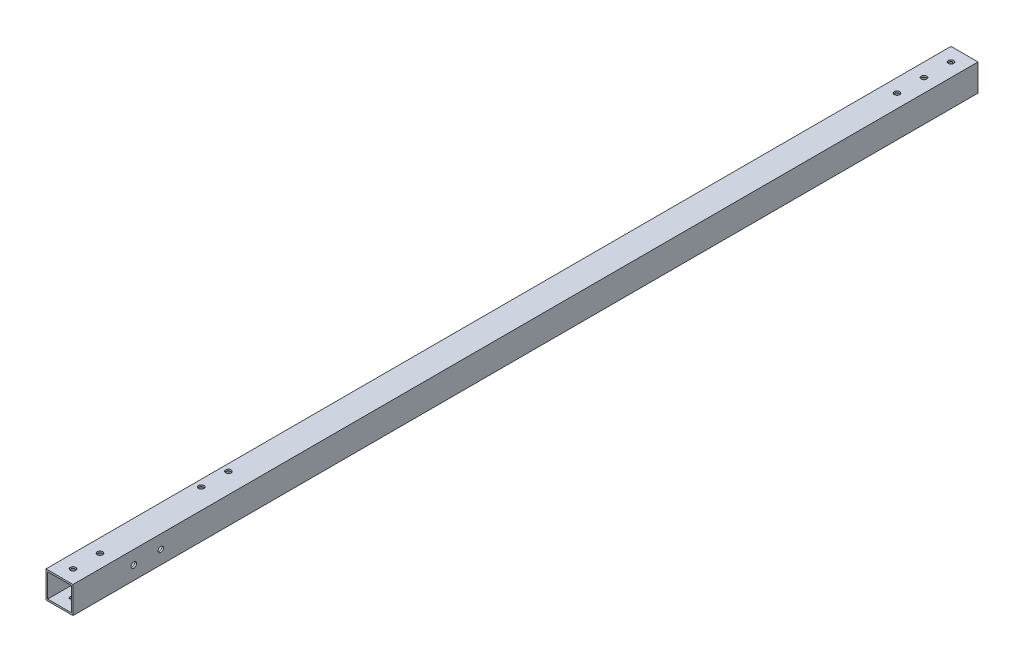
SolidWorks part; units mm, degrees
ref_plane "Front Plane" through (0, 0, 0) normal (0, 0, 1) x (1, 0, 0)
ref_plane "Top Plane" through (0, 0, 0) normal (0, 1, 0) x (1, 0, 0)
ref_plane "Right Plane" through (0, 0, 0) normal (1, 0, 0) x (0, 0, -1)
sketch "Sketch1" plane through (0, 0, 0) normal (0, 0, 1) x (1, 0, 0)
  line L1 (0, 0) -> (25.4, 0)
  line L2 (0, 0) -> (0, 25.4)
  line L3 (0, 25.4) -> (25.4, 25.4)
  line L4 (25.4, 0) -> (25.4, 25.4)
  line L5 (1.5875, 1.5875) -> (23.8125, 1.5875)
  line L6 (1.5875, 1.5875) -> (1.5875, 23.8125)
  line L7 (1.5875, 23.8125) -> (23.8125, 23.8125)
  line L8 (23.8125, 1.5875) -> (23.8125, 23.8125)
  dimension "D1" = 25.4
  dimension "D2" = 1.5875
  dimension "D3" = 1.5875
  dimension "D4" = 1.5875
  dimension "D5" = 1.5875
extrude "Boss-Extrude1" add sketch "Sketch1" along normal blind 850.9
sketch "Sketch3" plane through (0, 25.4, 0) normal (0, 1, 0) x (1, 0, 0)
  line L0 (0, -425.45) -> (25.4, -425.45) construction
  line L1 (25.4, -850.9) -> (25.4, 0) construction
  line L3 (25.4, -850.9) -> (0, -850.9) construction
  line L4 (0, -850.9) -> (0, 0) construction
  line L5 (25.4, 0) -> (0, 0) construction
  circle A12 centre (12.7, -812.8) radius 2.54
  circle A13 centre (12.7, -838.2) radius 2.54
  circle A14 centre (12.7, -12.7) radius 2.54
  circle A15 centre (12.7, -38.1) radius 2.54
  circle A16 centre (12.7, -63.5) radius 2.54
  circle A17 centre (6.35, -711.2) radius 2.54
  circle A18 centre (6.35, -685.8) radius 2.54
  point P24 (0, 0)
  point P25 (0, 0)
  point P26 (0, 0)
  point P27 (0, 0)
  dimension "D3" = 25.4
  dimension "D6" = 12.7
  dimension "D1" = 12.7
  dimension "D2" = 5.08
  dimension "D5" = 5.08
  dimension "D4" = 12.7
  dimension "D7" = 12.7
  dimension "D8" = 25.4
  dimension "D9" = 25.4
  dimension "D10" = 6.35
  dimension "D11" = 25.4
  dimension "D12" = 101.6
extrude "Cut-Extrude2" cut sketch "Sketch3" against normal through all
sketch "Sketch4" plane through (25.4, 0, 0) normal (1, 0, 0) x (0, 0, -1)
  line L0 (-850.9, 0) -> (-850.9, 25.4) construction
  circle A3 centre (-793.75, 12.7) radius 2.54
  circle A4 centre (-768.35, 12.7) radius 2.54
  dimension "D5" = 25.4
  dimension "D6" = 57.15
extrude "Cut-Extrude3" cut sketch "Sketch4" against normal through all
